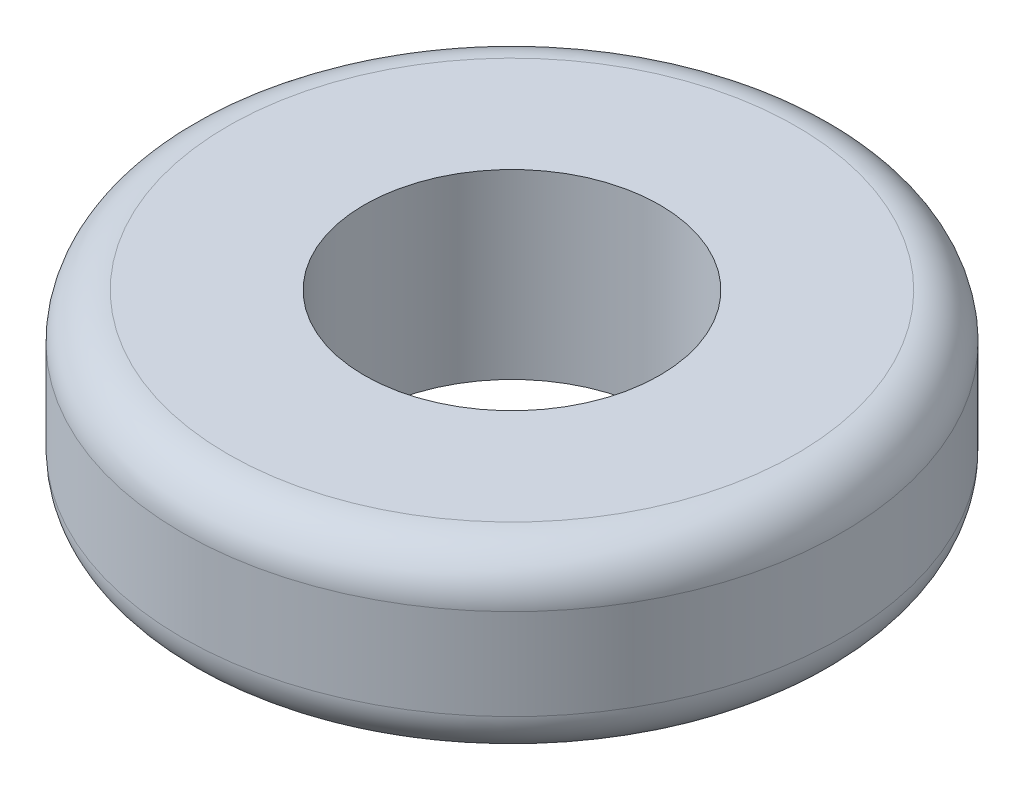
SolidWorks part; units mm, degrees
ref_plane "Front Plane" through (0, 0, 0) normal (0, 0, 1) x (1, 0, 0)
ref_plane "Top Plane" through (0, 0, 0) normal (0, 1, 0) x (1, 0, 0)
ref_plane "Right Plane" through (0, 0, 0) normal (1, 0, 0) x (0, 0, -1)
sketch "Sketch1" plane through (0, 0, 0) normal (0, 1, 0) x (1, 0, 0)
  circle A0 centre (0, 0) radius 3.25
  circle A1 centre (0, 0) radius 7.25
  dimension "D1" = 6.5
  dimension "D2" = 4
extrude "Boss-Extrude1" add sketch "Sketch1" along normal blind 4
fillet "Fillet1" radius 1 2 edges at (0, 4, 7.25) (0, 0, 7.25)
